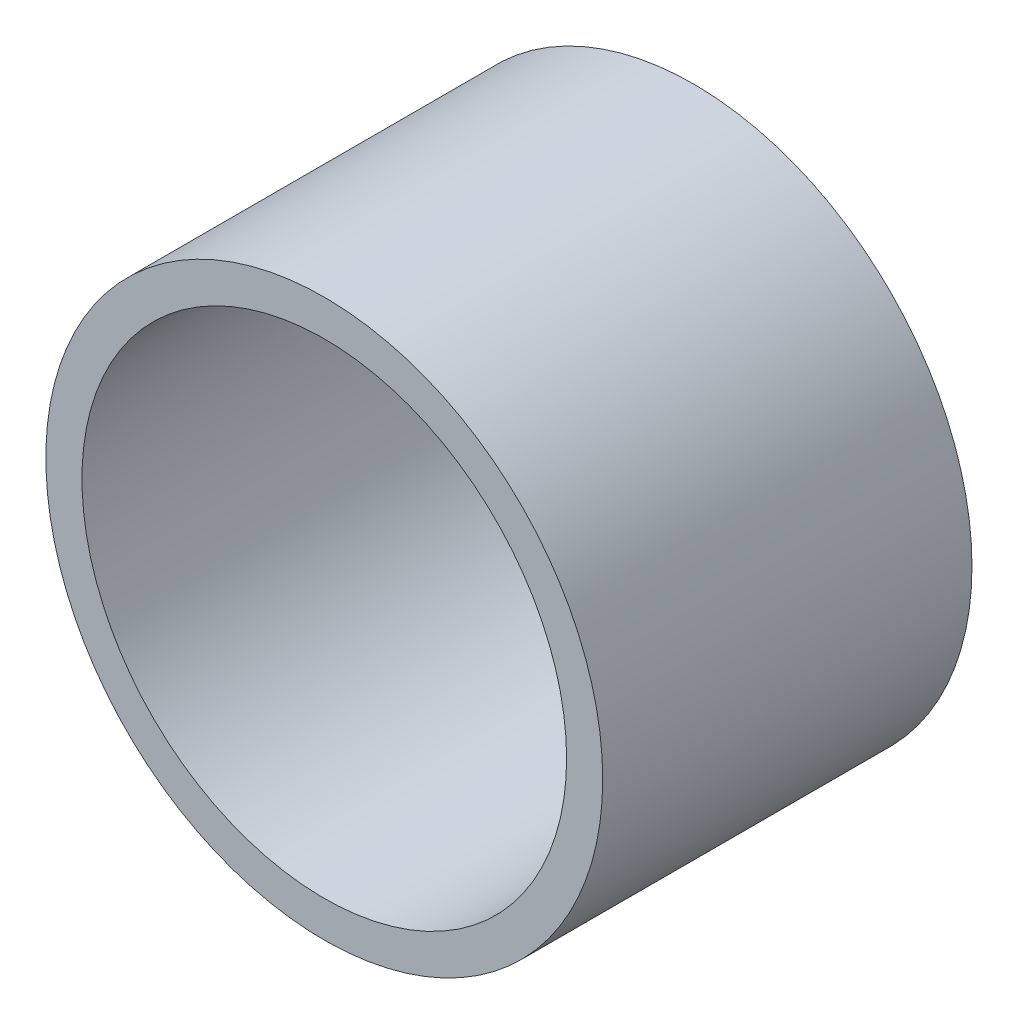
SolidWorks part; units mm, degrees
ref_plane "Front Plane" through (0, 0, 0) normal (0, 0, 1) x (1, 0, 0)
ref_plane "Top Plane" through (0, 0, 0) normal (0, 1, 0) x (1, 0, 0)
ref_plane "Right Plane" through (0, 0, 0) normal (1, 0, 0) x (0, 0, -1)
sketch "Sketch1" plane through (0, 0, 0) normal (0, 0, 1) x (1, 0, 0)
  circle A0 centre (0, 0) radius 30.1625
  dimension "Pipe OD" = 60.325
extrude "Extrude-Thin1" add sketch "Sketch1" along normal mid plane 40 thin thin type one direction reverse wall 3.9116
